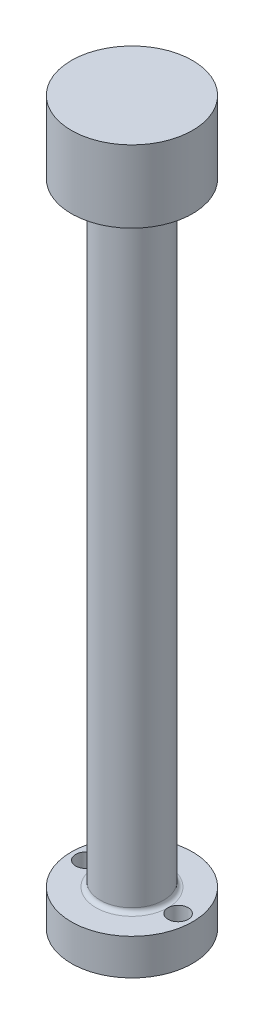
SolidWorks part; units mm, degrees
ref_plane "Front Plane" through (0, 0, 0) normal (0, 0, 1) x (1, 0, 0)
ref_plane "Top Plane" through (0, 0, 0) normal (0, 1, 0) x (1, 0, 0)
ref_plane "Right Plane" through (0, 0, 0) normal (1, 0, 0) x (0, 0, -1)
sketch "Sketch1" plane through (0, 0, 0) normal (0, 0, 1) x (1, 0, 0)
  line L0 (0, 0) -> (10.668, 0)
  line L1 (10.668, 0) -> (10.668, 6.35)
  line L2 (10.668, 6.35) -> (5.588, 6.35)
  line L3 (5.588, 6.35) -> (5.588, 114.3)
  line L4 (5.588, 114.3) -> (10.668, 114.3)
  line L5 (10.668, 114.3) -> (10.668, 127)
  line L6 (10.668, 127) -> (0, 127)
  line L7 (0, 127) -> (0, 0)
  dimension "D1" = 127
  dimension "D2" = 10.668
  dimension "D3" = 6.35
  dimension "D4" = 12.7
  dimension "D5" = 5.08
revolve "Revolve1" add sketch "Sketch1" angle 360 about L7
sketch "Sketch2" plane through (0, 6.35, 0) normal (0, 1, 0) x (1, 0, 0)
  line L0 (0, 0) -> (0, 10.668) construction
  line L2 (-5.588, 0) -> (-10.668, 0) construction
  circle A0 centre (-8.128, 0) radius 1.778
  circle A1 centre (0, 0) radius 10.668 construction
  circle A2 centre (0, 0) radius 5.588 construction
  circle A3 centre (0, 0) radius 5.588 construction
  circle A4 centre (8.128, 0) radius 1.778
  dimension "D1" = 3.556
extrude "Cut-Extrude1" cut sketch "Sketch2" against normal up to surface (6.35 mm away) up to face at (-10.668, 0, 0)
fillet "Fillet1" radius 1.27 1 edges at (-5.588, 114.3, 0)
fillet "Fillet2" radius 0.762 1 edges at (-5.588, 6.35, 0)
